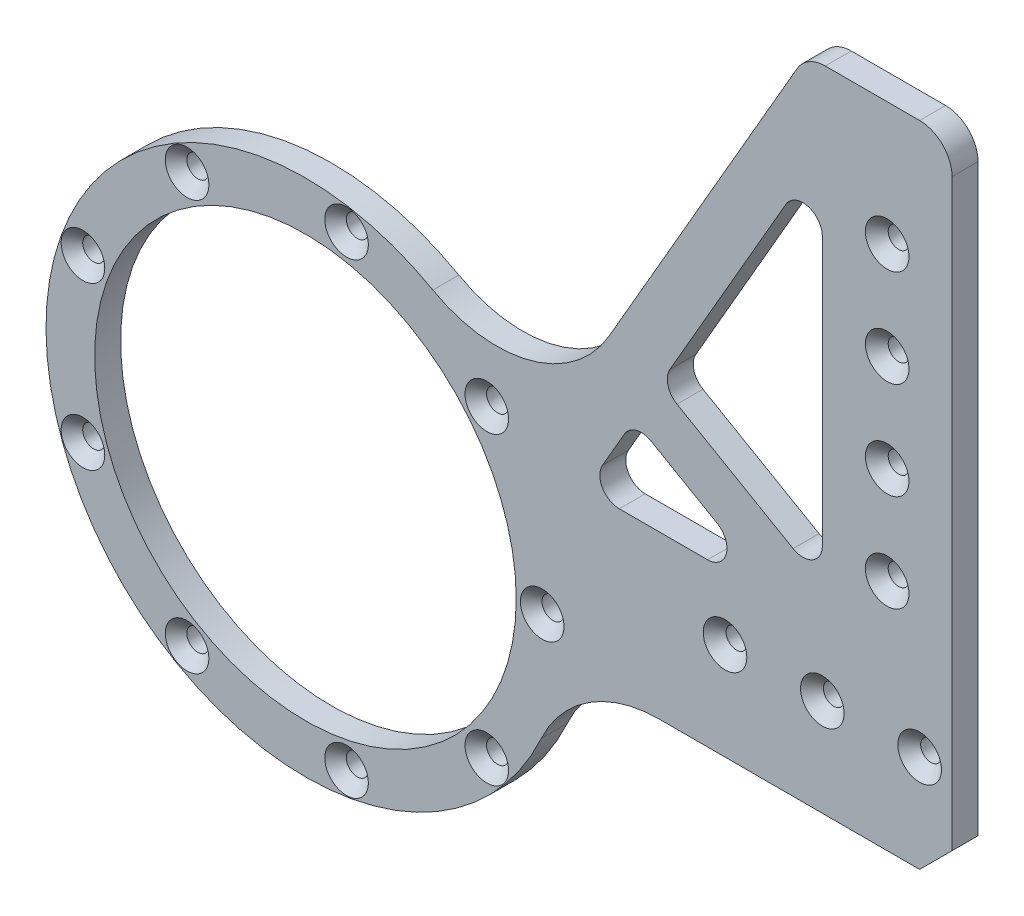
SolidWorks part; units mm, degrees
material "Thornel Mat VMA"
ref_plane "前视基准面" through (0, 0, 0) normal (0, 0, 1) x (1, 0, 0)
ref_plane "上视基准面" through (0, 0, 0) normal (0, 1, 0) x (1, 0, 0)
ref_plane "右视基准面" through (0, 0, 0) normal (1, 0, 0) x (0, 0, -1)
other "Configuration Table"
sketch "草图1" plane through (0, 0, 0) normal (0, 0, 1) x (1, 0, 0)
  circle A0 centre (0, 0) radius 40
  circle A10 centre (0, 0) radius 32.5
  dimension "D1" = 80
  dimension "D6" = 65
extrude "凸台-拉伸1" add sketch "草图1" along normal blind 4
sketch "草图2" plane through (0, 0, 4) normal (0, 0, 1) x (1, 0, 0)
  line L0 (0, 0) -> (40, 0) construction
  line L1 (0, 0) -> (36.5, 0) construction
  circle A0 centre (0, 0) radius 40 construction
  point P6 (36.5, 0)
  point P7 (27.9606, -23.4617)
  point P10 (6.3382, -35.9455)
  point P11 (-18.25, -31.6099)
  point P12 (-34.2988, -12.4837)
  point P13 (-34.2988, 12.4837)
  point P14 (-18.25, 31.6099)
  point P15 (6.3382, 35.9455)
  point P16 (27.9606, 23.4617)
  dimension "D3" = 36.5
  dimension "D2" = 9
hole_wizard "M3 六角凹锥坑螺钉的锥形沉头孔1" positions "草图2" profile "草图3" countersink size "M3" standard "ISO" end condition through all
sketch "草图3" plane through (27.9606, 23.4617, 4) normal (1, 0, 0) x (0, -1, 0)
  line L0 (0, 0) -> (0, 4)
  line L1 (0, 4) -> (1.7, 4)
  line L2 (1.7, 4) -> (1.7, 1.66)
  line L3 (1.7, 1.66) -> (3.36, 0)
  line L5 (3.36, 0) -> (0, 0)
  line L6 (-1.7, 1.66) -> (-3.36, 0) construction
  line L11 (0, -6.35) -> (0, 107.95) construction
  dimension "通孔孔直径" = 3.4
  dimension "通孔孔深度" = 4
  dimension "近端锥形沉头孔直径" = 6.72
  dimension "近端锥形沉头孔角度" = 90
sketch "草图4" plane through (0, 0, 4) normal (0, 0, 1) x (1, 0, 0)
  line L0 (0, 0) -> (40, 0) construction
  line L11 (39.6863, -5) -> (99.6863, -5)
  line L23 (77.2499, 95) -> (99.6863, 95)
  line L26 (99.6863, 95) -> (99.6863, -5)
  line L27 (77.2499, 95) -> (34.2914, 20.5937)
  line L28 (79.6863, 83.2199) -> (43.1863, 20) construction
  line L29 (43.1863, 20) -> (79.6863, 20) construction
  line L30 (79.6863, 20) -> (79.6863, 83.2199) construction
  line L32 (54.6863, 39.9186) -> (79.6863, 25.4848)
  line L33 (50.6863, 32.9904) -> (73.1863, 20)
  line L34 (79.6863, 83.2199) -> (54.6863, 39.9186)
  line L35 (79.6863, 83.2199) -> (79.6863, 25.4848)
  line L36 (50.6863, 32.9904) -> (43.1863, 20)
  line L37 (43.1863, 20) -> (73.1863, 20)
  line L38 (89.6863, 95) -> (89.6863, -5) construction
  circle A0 centre (0, 0) radius 40 construction
  circle A5 centre (79.6863, 10) radius 1.55 construction
  circle A13 centre (94.6863, 10) radius 1.55 construction
  circle A29 centre (64.6863, 10) radius 1.55 construction
  circle A34 centre (89.6863, 76) radius 1.55 construction
  arc A42 (34.2914, 20.5937) -> (39.6863, -5) centre (0, 0) cw
  circle A43 centre (89.6863, 61) radius 1.55 construction
  circle A44 centre (89.6863, 46) radius 1.55 construction
  circle A45 centre (89.6863, 31) radius 1.55 construction
  point P32 (89.6863, 76)
  point P34 (89.6863, 61)
  point P35 (89.6863, 46)
  point P36 (89.6863, 31)
  point P37 (79.6863, 10)
  point P38 (64.6863, 10)
  point P39 (94.6863, 10)
  dimension "D1" = 5
  dimension "D2" = 20
  dimension "D8" = 3.1
  dimension "D9" = 3.1
  dimension "D10" = 15
  dimension "D15" = 15
  dimension "D16" = 15
  dimension "D18" = 10
  dimension "D19" = 3.1
  dimension "D25" = 15
  dimension "D26" = 50
  dimension "D27" = 3.1
  dimension "D6" = 60
  dimension "D11" = 15
  dimension "D3" = 60
  dimension "D14" = 3.1
  dimension "D20" = 3.1
  dimension "D21" = 3.1
  dimension "D4" = 100
  dimension "D5" = 25
  dimension "D7" = 8
  dimension "D12" = 15
  dimension "D13" = 5
  dimension "D17" = 8
  dimension "D22" = 19
  dimension "D23" = 15
  dimension "D24" = 15
  dimension "D28" = 15
extrude "凸台-拉伸2" add sketch "草图4" against normal up to surface (4 mm away) up to face at (38.2, 0, 0)
sketch "草图8" plane through (0, 0, 4) normal (0, 0, 1) x (1, 0, 0)
  line L38 (89.6863, 95) -> (89.6863, -5) construction
  line L39 (99.6863, -5) -> (99.6863, 95) construction
  circle A5 centre (79.6863, 10) radius 1.55 construction
  circle A13 centre (94.6863, 10) radius 1.55 construction
  circle A29 centre (64.6863, 10) radius 1.55 construction
  circle A34 centre (89.6863, 76) radius 1.55 construction
  circle A43 centre (89.6863, 61) radius 1.55 construction
  circle A44 centre (89.6863, 46) radius 1.55 construction
  circle A45 centre (89.6863, 31) radius 1.55 construction
  point P32 (89.6863, 76)
  point P34 (89.6863, 61)
  point P35 (89.6863, 46)
  point P36 (89.6863, 31)
  point P37 (79.6863, 10)
  point P38 (64.6863, 10)
  point P39 (94.6863, 10)
  dimension "D8" = 3.1
  dimension "D9" = 3.1
  dimension "D15" = 15
  dimension "D19" = 3.1
  dimension "D27" = 3.1
  dimension "D14" = 3.1
  dimension "D20" = 3.1
  dimension "D21" = 3.1
  dimension "D12" = 15
  dimension "D23" = 15
  dimension "D24" = 15
  dimension "D28" = 15
fillet "圆角1" [suppressed] radius 10
fillet "圆角2" radius 20 2 edges at (39.6863, -5, 2) (34.2914, 20.5937, 2)
fillet "圆角3" [suppressed] radius 20
chamfer "倒角1" distance 5 angle 45 1 edges at (99.6863, -5, 2)
fillet "圆角4" radius 3 6 edges at (43.1863, 20, 2) (50.6863, 32.9904, 2) (73.1863, 20, 2) (54.6863, 39.9186, 2) (79.6863, 83.2199, 2) (79.6863, 25.4848, 2)
fillet "圆角5" radius 5 2 edges at (77.2499, 95, 2) (99.6863, 95, 2)
hole_wizard "M3 六角凹锥坑螺钉的锥形沉头孔3" positions "草图8" profile "草图9" countersink size "M3" standard "ISO" end condition through all
sketch "草图9" plane through (94.6863, 10, 4) normal (1, 0, 0) x (0, -1, 0)
  line L0 (0, 0) -> (0, 4)
  line L1 (0, 4) -> (1.6, 4)
  line L2 (1.6, 4) -> (1.6, 1.76)
  line L3 (1.6, 1.76) -> (3.36, 0)
  line L5 (3.36, 0) -> (0, 0)
  line L6 (-1.6, 1.76) -> (-3.36, 0) construction
  line L11 (0, -6.35) -> (0, 107.95) construction
  dimension "通孔孔直径" = 3.2
  dimension "通孔孔深度" = 4
  dimension "近端锥形沉头孔直径" = 6.72
  dimension "近端锥形沉头孔角度" = 90
